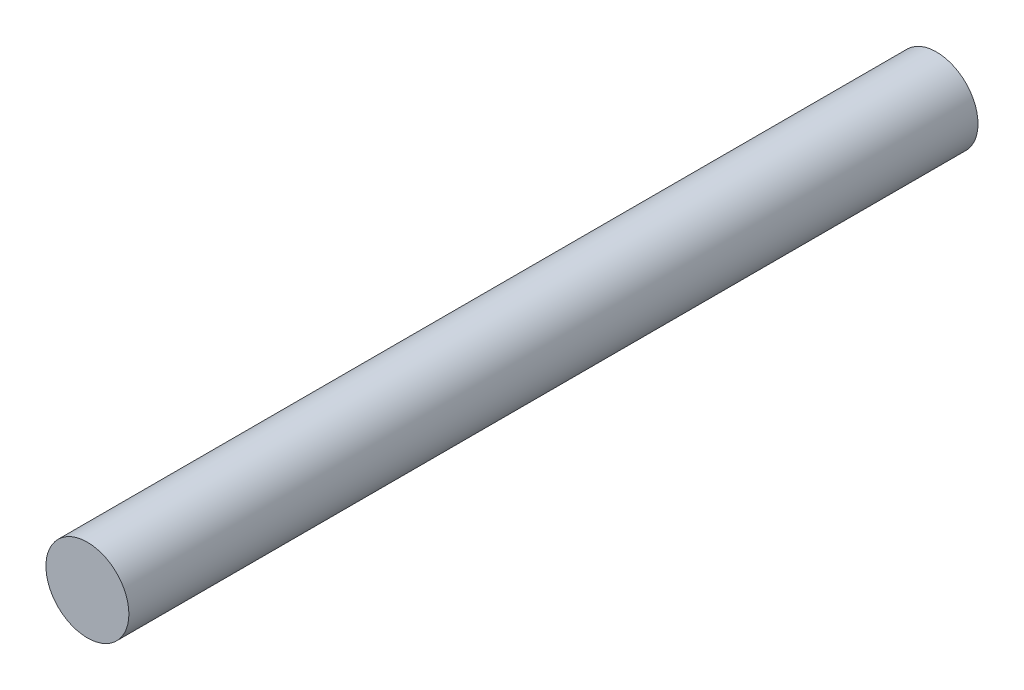
SolidWorks part; units mm, degrees
ref_plane "Front Plane" through (0, 0, 0) normal (0, 0, 1) x (1, 0, 0)
ref_plane "Top Plane" through (0, 0, 0) normal (0, 1, 0) x (1, 0, 0)
ref_plane "Right Plane" through (0, 0, 0) normal (1, 0, 0) x (0, 0, -1)
sketch "Sketch1" plane through (0, 0, 0) normal (0, 0, 1) x (1, 0, 0)
  circle A0 centre (-67.8901, 12.1393) radius 6.35
  dimension "D1" = 12.7
extrude "Boss-Extrude1" add sketch "Sketch1" along normal blind 130
